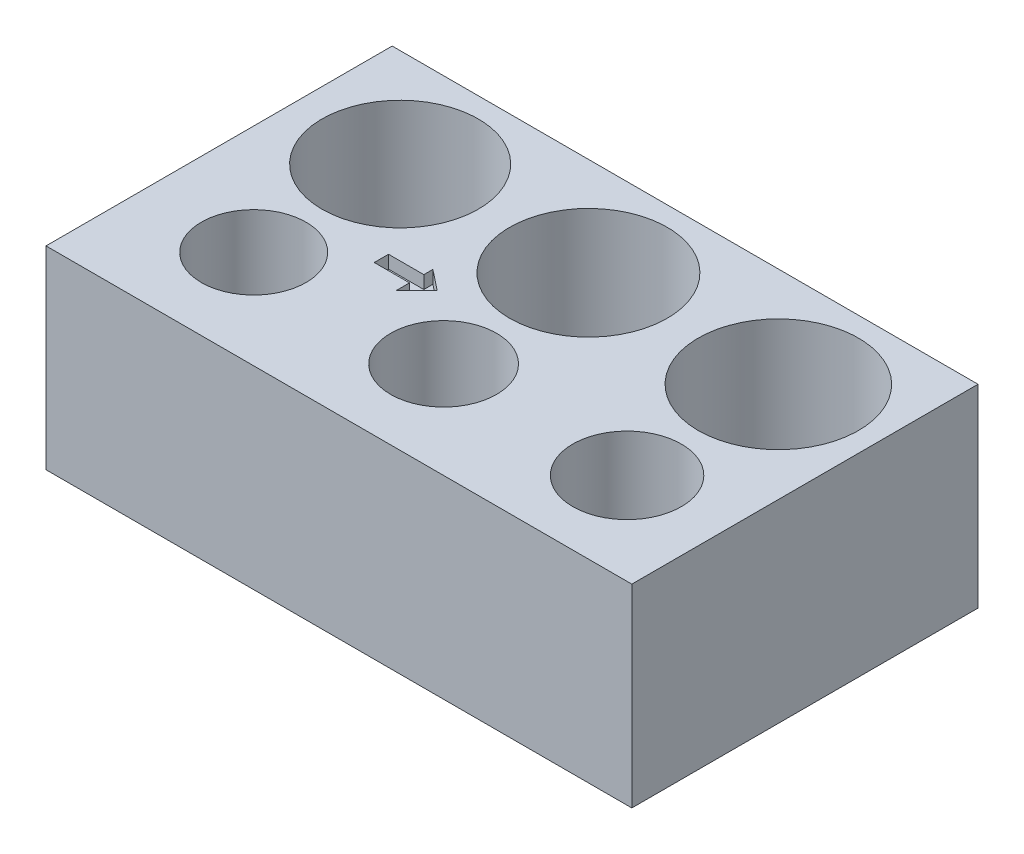
SolidWorks part; units mm, degrees
ref_plane "Front Plane" through (0, 0, 0) normal (0, 0, 1) x (1, 0, 0)
ref_plane "Top Plane" through (0, 0, 0) normal (0, 1, 0) x (1, 0, 0)
ref_plane "Right Plane" through (0, 0, 0) normal (1, 0, 0) x (0, 0, -1)
sketch "Sketch1" plane through (0, 0, 0) normal (0, 1, 0) x (1, 0, 0)
  line L1 (-22.662, 13.3917) -> (22.662, 13.3917)
  line L2 (-22.662, 13.3917) -> (-22.662, -13.3917)
  line L3 (-22.662, -13.3917) -> (22.662, -13.3917)
  line L4 (22.662, 13.3917) -> (22.662, -13.3917)
  line L5 (-22.662, 13.3917) -> (22.662, -13.3917) construction
  line L6 (-22.662, -13.3917) -> (22.662, 13.3917) construction
  circle A0 centre (-14.1949, -5.79) radius 4.05
  circle A1 centre (0.6226, -5.9145) radius 4.1
  circle A2 centre (15.191, -6.2881) radius 4.2
  circle A3 centre (-14.4439, 5.79) radius 6.05
  circle A4 centre (0.1245, 5.79) radius 6.1
  circle A5 centre (14.9419, 5.6655) radius 6.2
  point P0 (0, 0)
  dimension "D1" = 8.1
  dimension "D2" = 8.2
  dimension "D3" = 8.4
  dimension "D4" = 12.1
  dimension "D5" = 12.2
  dimension "D6" = 12.4
extrude "Boss-Extrude1" add sketch "Sketch1" along normal blind 15
sketch "Sketch2" plane through (0, 15, 0) normal (0, 1, 0) x (1, 0, 0)
  line L0 (-6.1221, 0) -> (-6.1221, -0.7007)
  line L1 (-8.8513, -0.7007) -> (-6.1221, -0.7007)
  line L2 (-8.8513, -0.7007) -> (-8.8513, -1.8071)
  line L3 (-8.8513, -1.8071) -> (-6.1221, -1.8071)
  line L5 (-6.1221, -2.8398) -> (-4.5363, -1.2539)
  line L6 (-4.5363, -1.2539) -> (-6.1221, 0)
  line L7 (-6.1221, -1.8071) -> (-6.1221, -2.8398)
extrude "Cut-Extrude1" cut sketch "Sketch2" against normal blind 1
